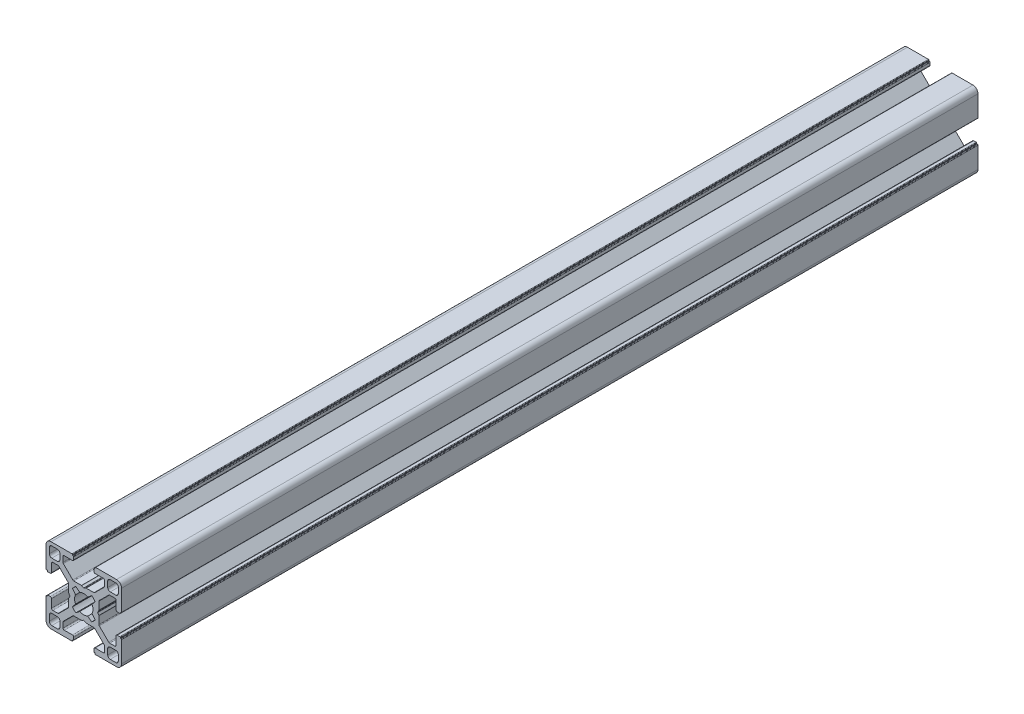
SolidWorks part; units mm, degrees
ref_plane "Alzado" through (0, 0, 0) normal (0, 0, 1) x (1, 0, 0)
ref_plane "Planta" through (0, 0, 0) normal (0, 1, 0) x (1, 0, 0)
ref_plane "Vista lateral" through (0, 0, 0) normal (1, 0, 0) x (0, 0, -1)
ref_plane "Plano1" through (0, 0, 1000) normal (0, 0, 1) x (1, 0, 0)
sketch "Croquis1" plane through (0, 0, 1000) normal (0, 0, 1) x (1, 0, 0)
  line L0 (8, -5.5) -> (5.8, -5.5)
  line L1 (4.8, -4.5) -> (4.8, -2.3)
  line L2 (5.8, -1.3) -> (8, -1.3)
  line L3 (9, -2.3) -> (9, -4.5)
  line L4 (-15.2, -5.5) -> (-17.4, -5.5)
  line L5 (-18.4, -4.5) -> (-18.4, -2.3)
  line L6 (-17.4, -1.3) -> (-15.2, -1.3)
  line L7 (-14.2, -2.3) -> (-14.2, -4.5)
  line L8 (-17.4, -24.5) -> (-15.2, -24.5)
  line L9 (-14.2, -25.5) -> (-14.2, -27.7)
  line L10 (-15.2, -28.7) -> (-17.4, -28.7)
  line L11 (-18.4, -27.7) -> (-18.4, -25.5)
  line L12 (5.8, -24.5) -> (8, -24.5)
  line L13 (9, -25.5) -> (9, -27.7)
  line L14 (8, -28.7) -> (5.8, -28.7)
  line L15 (4.8, -27.7) -> (4.8, -25.5)
  line L16 (-7.8359, -10.4816) -> (-6.3001, -11.7194)
  line L17 (-3.0999, -11.7194) -> (-1.5641, -10.4816)
  line L18 (-0.1947, -11.8453) -> (-1.4194, -13.3999)
  line L19 (-1.4194, -16.6001) -> (-0.1947, -18.1547)
  line L20 (-1.5641, -19.5184) -> (-3.0999, -18.2806)
  line L21 (-6.3001, -18.2806) -> (-7.8359, -19.5184)
  line L22 (-9.2053, -18.1547) -> (-7.9806, -16.6001)
  line L23 (-7.9806, -13.3999) -> (-9.2053, -11.8453)
  line L24 (9.8, -10.5) -> (10.1, -10.5)
  line L25 (10.3, -10.3) -> (10.3, -2)
  line L26 (8.3, 0) -> (0, 0)
  line L27 (-0.2, -0.2) -> (-0.2, -0.5)
  line L28 (-0.2, -0.5) -> (-0.5, -0.5)
  line L29 (-0.7, -0.7) -> (-0.7, -1.7)
  line L30 (-0.2, -2.2) -> (3.05, -2.2)
  line L31 (3.55, -2.7) -> (3.55, -4.7431)
  line L32 (3.4037, -5.0964) -> (-0.3491, -8.8534)
  line L33 (-0.7028, -9) -> (-3.7468, -9)
  line L34 (-3.8462, -9.0264) -> (-4.6006, -9.4583)
  line L35 (-4.7994, -9.4583) -> (-5.5538, -9.0264)
  line L36 (-5.6532, -9) -> (-8.6972, -9)
  line L37 (-9.0509, -8.8534) -> (-12.8037, -5.0964)
  line L38 (-12.95, -4.7431) -> (-12.95, -2.7)
  line L39 (-12.45, -2.2) -> (-9.2, -2.2)
  line L40 (-8.7, -1.7) -> (-8.7, -0.7)
  line L41 (-8.9, -0.5) -> (-9.2, -0.5)
  line L42 (-9.2, -0.5) -> (-9.2, -0.2)
  line L43 (-9.4, 0) -> (-17.7, 0)
  line L44 (-19.7, -2) -> (-19.7, -10.3)
  line L45 (-19.5, -10.5) -> (-19.2, -10.5)
  line L46 (-19.2, -10.5) -> (-19.2, -10.8)
  line L47 (-19, -11) -> (-18, -11)
  line L48 (-17.5, -10.5) -> (-17.5, -7.25)
  line L49 (-17, -6.75) -> (-14.9569, -6.75)
  line L50 (-14.6036, -6.8963) -> (-10.8466, -10.6491)
  line L51 (-10.7, -11.0028) -> (-10.7, -14.0468)
  line L52 (-10.6736, -14.1462) -> (-10.2417, -14.9006)
  line L53 (-10.2417, -15.0994) -> (-10.6736, -15.8538)
  line L54 (-10.7, -15.9532) -> (-10.7, -18.9972)
  line L55 (-10.8466, -19.3509) -> (-14.6036, -23.1037)
  line L56 (-14.9569, -23.25) -> (-17, -23.25)
  line L57 (-17.5, -22.75) -> (-17.5, -19.5)
  line L58 (-18, -19) -> (-19, -19)
  line L59 (-19.2, -19.2) -> (-19.2, -19.5)
  line L60 (-19.2, -19.5) -> (-19.5, -19.5)
  line L61 (-19.7, -19.7) -> (-19.7, -28)
  line L62 (-17.7, -30) -> (-9.4, -30)
  line L63 (-9.2, -29.8) -> (-9.2, -29.5)
  line L64 (-9.2, -29.5) -> (-8.9, -29.5)
  line L65 (-8.7, -29.3) -> (-8.7, -28.3)
  line L66 (-9.2, -27.8) -> (-12.45, -27.8)
  line L67 (-12.95, -27.3) -> (-12.95, -25.2569)
  line L68 (-12.8037, -24.9036) -> (-9.0509, -21.1466)
  line L69 (-8.6972, -21) -> (-5.6532, -21)
  line L70 (-5.5538, -20.9736) -> (-4.7994, -20.5417)
  line L71 (-4.6006, -20.5417) -> (-3.8462, -20.9736)
  line L72 (-3.7468, -21) -> (-0.7028, -21)
  line L73 (-0.3491, -21.1466) -> (3.4037, -24.9036)
  line L74 (3.55, -25.2569) -> (3.55, -27.3)
  line L75 (3.05, -27.8) -> (-0.2, -27.8)
  line L76 (-0.7, -28.3) -> (-0.7, -29.3)
  line L77 (-0.5, -29.5) -> (-0.2, -29.5)
  line L78 (-0.2, -29.5) -> (-0.2, -29.8)
  line L79 (0, -30) -> (8.3, -30)
  line L80 (10.3, -28) -> (10.3, -19.7)
  line L81 (10.1, -19.5) -> (9.8, -19.5)
  line L82 (9.8, -19.5) -> (9.8, -19.2)
  line L83 (9.6, -19) -> (8.6, -19)
  line L84 (8.1, -19.5) -> (8.1, -22.75)
  line L85 (7.6, -23.25) -> (5.5569, -23.25)
  line L86 (5.2036, -23.1037) -> (1.4466, -19.3509)
  line L87 (1.3, -18.9972) -> (1.3, -15.9532)
  line L88 (1.2736, -15.8538) -> (0.8417, -15.0994)
  line L89 (0.8417, -14.9006) -> (1.2736, -14.1462)
  line L90 (1.3, -14.0468) -> (1.3, -11.0028)
  line L91 (1.4466, -10.6491) -> (5.2036, -6.8963)
  line L92 (5.5569, -6.75) -> (7.6, -6.75)
  line L93 (8.1, -7.25) -> (8.1, -10.5)
  line L94 (8.6, -11) -> (9.6, -11)
  line L95 (9.8, -10.8) -> (9.8, -10.5)
  arc A0 (9, -4.5) -> (8, -5.5) centre (8, -4.5) cw
  arc A1 (5.8, -5.5) -> (4.8, -4.5) centre (5.8, -4.5) cw
  arc A2 (4.8, -2.3) -> (5.8, -1.3) centre (5.8, -2.3) cw
  arc A3 (8, -1.3) -> (9, -2.3) centre (8, -2.3) cw
  arc A4 (-14.2, -4.5) -> (-15.2, -5.5) centre (-15.2, -4.5) cw
  arc A5 (-17.4, -5.5) -> (-18.4, -4.5) centre (-17.4, -4.5) cw
  arc A6 (-18.4, -2.3) -> (-17.4, -1.3) centre (-17.4, -2.3) cw
  arc A7 (-15.2, -1.3) -> (-14.2, -2.3) centre (-15.2, -2.3) cw
  arc A8 (-18.4, -25.5) -> (-17.4, -24.5) centre (-17.4, -25.5) cw
  arc A9 (-15.2, -24.5) -> (-14.2, -25.5) centre (-15.2, -25.5) cw
  arc A10 (-14.2, -27.7) -> (-15.2, -28.7) centre (-15.2, -27.7) cw
  arc A11 (-17.4, -28.7) -> (-18.4, -27.7) centre (-17.4, -27.7) cw
  arc A12 (4.8, -25.5) -> (5.8, -24.5) centre (5.8, -25.5) cw
  arc A13 (8, -24.5) -> (9, -25.5) centre (8, -25.5) cw
  arc A14 (9, -27.7) -> (8, -28.7) centre (8, -27.7) cw
  arc A15 (5.8, -28.7) -> (4.8, -27.7) centre (5.8, -27.7) cw
  arc A16 (-9.2053, -11.8453) -> (-7.8359, -10.4816) centre (-4.7, -15) cw
  arc A17 (-6.3001, -11.7194) -> (-3.0999, -11.7194) centre (-4.7, -15) cw
  arc A18 (-1.5641, -10.4816) -> (-0.1947, -11.8453) centre (-4.7, -15) cw
  arc A19 (-1.4194, -13.3999) -> (-1.4194, -16.6001) centre (-4.7, -15) cw
  arc A20 (-0.1947, -18.1547) -> (-1.5641, -19.5184) centre (-4.7, -15) cw
  arc A21 (-3.0999, -18.2806) -> (-6.3001, -18.2806) centre (-4.7, -15) cw
  arc A22 (-7.8359, -19.5184) -> (-9.2053, -18.1547) centre (-4.7, -15) cw
  arc A23 (-7.9806, -16.6001) -> (-7.9806, -13.3999) centre (-4.7, -15) cw
  arc A24 (10.1, -10.5) -> (10.3, -10.3) centre (10.1, -10.3) ccw
  arc A25 (10.3, -2) -> (8.3, 0) centre (8.3, -2) ccw
  arc A26 (0, 0) -> (-0.2, -0.2) centre (0, -0.2) ccw
  arc A27 (-0.5, -0.5) -> (-0.7, -0.7) centre (-0.5, -0.7) ccw
  arc A28 (-0.7, -1.7) -> (-0.2, -2.2) centre (-0.2, -1.7) ccw
  arc A29 (3.05, -2.2) -> (3.55, -2.7) centre (3.05, -2.7) cw
  arc A30 (3.55, -4.7431) -> (3.4037, -5.0964) centre (3.05, -4.7431) cw
  arc A31 (-0.3491, -8.8534) -> (-0.7028, -9) centre (-0.7028, -8.5) cw
  arc A32 (-3.7468, -9) -> (-3.8462, -9.0264) centre (-3.7468, -9.2) ccw
  arc A33 (-4.6006, -9.4583) -> (-4.7994, -9.4583) centre (-4.7, -9.2847) cw
  arc A34 (-5.5538, -9.0264) -> (-5.6532, -9) centre (-5.6532, -9.2) ccw
  arc A35 (-8.6972, -9) -> (-9.0509, -8.8534) centre (-8.6972, -8.5) cw
  arc A36 (-12.8037, -5.0964) -> (-12.95, -4.7431) centre (-12.45, -4.7431) cw
  arc A37 (-12.95, -2.7) -> (-12.45, -2.2) centre (-12.45, -2.7) cw
  arc A38 (-9.2, -2.2) -> (-8.7, -1.7) centre (-9.2, -1.7) ccw
  arc A39 (-8.7, -0.7) -> (-8.9, -0.5) centre (-8.9, -0.7) ccw
  arc A40 (-9.2, -0.2) -> (-9.4, 0) centre (-9.4, -0.2) ccw
  arc A41 (-17.7, 0) -> (-19.7, -2) centre (-17.7, -2) ccw
  arc A42 (-19.7, -10.3) -> (-19.5, -10.5) centre (-19.5, -10.3) ccw
  arc A43 (-19.2, -10.8) -> (-19, -11) centre (-19, -10.8) ccw
  arc A44 (-18, -11) -> (-17.5, -10.5) centre (-18, -10.5) ccw
  arc A45 (-17.5, -7.25) -> (-17, -6.75) centre (-17, -7.25) cw
  arc A46 (-14.9569, -6.75) -> (-14.6036, -6.8963) centre (-14.9569, -7.25) cw
  arc A47 (-10.8466, -10.6491) -> (-10.7, -11.0028) centre (-11.2, -11.0028) cw
  arc A48 (-10.7, -14.0468) -> (-10.6736, -14.1462) centre (-10.5, -14.0468) ccw
  arc A49 (-10.2417, -14.9006) -> (-10.2417, -15.0994) centre (-10.4153, -15) cw
  arc A50 (-10.6736, -15.8538) -> (-10.7, -15.9532) centre (-10.5, -15.9532) ccw
  arc A51 (-10.7, -18.9972) -> (-10.8466, -19.3509) centre (-11.2, -18.9972) cw
  arc A52 (-14.6036, -23.1037) -> (-14.9569, -23.25) centre (-14.9569, -22.75) cw
  arc A53 (-17, -23.25) -> (-17.5, -22.75) centre (-17, -22.75) cw
  arc A54 (-17.5, -19.5) -> (-18, -19) centre (-18, -19.5) ccw
  arc A55 (-19, -19) -> (-19.2, -19.2) centre (-19, -19.2) ccw
  arc A56 (-19.5, -19.5) -> (-19.7, -19.7) centre (-19.5, -19.7) ccw
  arc A57 (-19.7, -28) -> (-17.7, -30) centre (-17.7, -28) ccw
  arc A58 (-9.4, -30) -> (-9.2, -29.8) centre (-9.4, -29.8) ccw
  arc A59 (-8.9, -29.5) -> (-8.7, -29.3) centre (-8.9, -29.3) ccw
  arc A60 (-8.7, -28.3) -> (-9.2, -27.8) centre (-9.2, -28.3) ccw
  arc A61 (-12.45, -27.8) -> (-12.95, -27.3) centre (-12.45, -27.3) cw
  arc A62 (-12.95, -25.2569) -> (-12.8037, -24.9036) centre (-12.45, -25.2569) cw
  arc A63 (-9.0509, -21.1466) -> (-8.6972, -21) centre (-8.6972, -21.5) cw
  arc A64 (-5.6532, -21) -> (-5.5538, -20.9736) centre (-5.6532, -20.8) ccw
  arc A65 (-4.7994, -20.5417) -> (-4.6006, -20.5417) centre (-4.7, -20.7153) cw
  arc A66 (-3.8462, -20.9736) -> (-3.7468, -21) centre (-3.7468, -20.8) ccw
  arc A67 (-0.7028, -21) -> (-0.3491, -21.1466) centre (-0.7028, -21.5) cw
  arc A68 (3.4037, -24.9036) -> (3.55, -25.2569) centre (3.05, -25.2569) cw
  arc A69 (3.55, -27.3) -> (3.05, -27.8) centre (3.05, -27.3) cw
  arc A70 (-0.2, -27.8) -> (-0.7, -28.3) centre (-0.2, -28.3) ccw
  arc A71 (-0.7, -29.3) -> (-0.5, -29.5) centre (-0.5, -29.3) ccw
  arc A72 (-0.2, -29.8) -> (0, -30) centre (0, -29.8) ccw
  arc A73 (8.3, -30) -> (10.3, -28) centre (8.3, -28) ccw
  arc A74 (10.3, -19.7) -> (10.1, -19.5) centre (10.1, -19.7) ccw
  arc A75 (9.8, -19.2) -> (9.6, -19) centre (9.6, -19.2) ccw
  arc A76 (8.6, -19) -> (8.1, -19.5) centre (8.6, -19.5) ccw
  arc A77 (8.1, -22.75) -> (7.6, -23.25) centre (7.6, -22.75) cw
  arc A78 (5.5569, -23.25) -> (5.2036, -23.1037) centre (5.5569, -22.75) cw
  arc A79 (1.4466, -19.3509) -> (1.3, -18.9972) centre (1.8, -18.9972) cw
  arc A80 (1.3, -15.9532) -> (1.2736, -15.8538) centre (1.1, -15.9532) ccw
  arc A81 (0.8417, -15.0994) -> (0.8417, -14.9006) centre (1.0153, -15) cw
  arc A82 (1.2736, -14.1462) -> (1.3, -14.0468) centre (1.1, -14.0468) ccw
  arc A83 (1.3, -11.0028) -> (1.4466, -10.6491) centre (1.8, -11.0028) cw
  arc A84 (5.2036, -6.8963) -> (5.5569, -6.75) centre (5.5569, -7.25) cw
  arc A85 (7.6, -6.75) -> (8.1, -7.25) centre (7.6, -7.25) cw
  arc A86 (8.1, -10.5) -> (8.6, -11) centre (8.6, -10.5) ccw
  arc A87 (9.6, -11) -> (9.8, -10.8) centre (9.6, -10.8) ccw
extrude "Saliente-Extruir1" add sketch "Croquis1" against normal blind 1000
sketch "Croquis4" plane through (0, 0, 0) normal (0, 0, -1) x (-1, 0, 0)
  line L72 (-9.8, -10.5) -> (-9.8, -10.8)
  line L73 (-9.6, -11) -> (-8.6, -11)
  line L74 (-8.1, -10.5) -> (-8.1, -7.25)
  line L75 (-7.6, -6.75) -> (-5.5569, -6.75)
  line L76 (-5.2036, -6.8963) -> (-1.4466, -10.6491)
  line L77 (-1.3, -11.0028) -> (-1.3, -14.0468)
  line L78 (-1.2736, -14.1462) -> (-0.8417, -14.9006)
  line L79 (-0.8417, -15.0994) -> (-1.2736, -15.8538)
  line L80 (-1.3, -15.9532) -> (-1.3, -18.9972)
  line L81 (-1.4466, -19.3509) -> (-5.2036, -23.1037)
  line L82 (-5.5569, -23.25) -> (-7.6, -23.25)
  line L83 (-8.1, -22.75) -> (-8.1, -19.5)
  line L84 (-8.6, -19) -> (-9.6, -19)
  line L85 (-9.8, -19.2) -> (-9.8, -19.5)
  line L86 (-9.8, -19.5) -> (-10.1, -19.5)
  line L87 (-10.3, -19.7) -> (-10.3, -28)
  line L88 (-8.3, -30) -> (0, -30)
  line L89 (0.2, -29.8) -> (0.2, -29.5)
  line L90 (0.2, -29.5) -> (0.5, -29.5)
  line L91 (0.7, -29.3) -> (0.7, -28.3)
  line L92 (0.2, -27.8) -> (-3.05, -27.8)
  line L93 (-3.55, -27.3) -> (-3.55, -25.2569)
  line L94 (-3.4037, -24.9036) -> (0.3491, -21.1466)
  line L95 (0.7028, -21) -> (3.7468, -21)
  line L96 (3.8462, -20.9736) -> (4.6006, -20.5417)
  line L97 (4.7994, -20.5417) -> (5.5538, -20.9736)
  line L98 (5.6532, -21) -> (8.6972, -21)
  line L99 (9.0509, -21.1466) -> (12.8037, -24.9036)
  line L100 (12.95, -25.2569) -> (12.95, -27.3)
  line L101 (12.45, -27.8) -> (9.2, -27.8)
  line L102 (8.7, -28.3) -> (8.7, -29.3)
  line L103 (8.9, -29.5) -> (9.2, -29.5)
  line L104 (9.2, -29.5) -> (9.2, -29.8)
  line L105 (9.4, -30) -> (17.7, -30)
  line L106 (19.7, -28) -> (19.7, -19.7)
  line L107 (19.5, -19.5) -> (19.2, -19.5)
  line L108 (19.2, -19.5) -> (19.2, -19.2)
  line L109 (19, -19) -> (18, -19)
  line L110 (17.5, -19.5) -> (17.5, -22.75)
  line L111 (17, -23.25) -> (14.9569, -23.25)
  line L112 (14.6036, -23.1037) -> (10.8466, -19.3509)
  line L113 (10.7, -18.9972) -> (10.7, -15.9532)
  line L114 (10.6736, -15.8538) -> (10.2417, -15.0994)
  line L115 (10.2417, -14.9006) -> (10.6736, -14.1462)
  line L116 (10.7, -14.0468) -> (10.7, -11.0028)
  line L117 (10.8466, -10.6491) -> (14.6036, -6.8963)
  line L118 (14.9569, -6.75) -> (17, -6.75)
  line L119 (17.5, -7.25) -> (17.5, -10.5)
  line L120 (18, -11) -> (19, -11)
  line L121 (19.2, -10.8) -> (19.2, -10.5)
  line L122 (19.2, -10.5) -> (19.5, -10.5)
  line L123 (19.7, -10.3) -> (19.7, -2)
  line L124 (17.7, 0) -> (9.4, 0)
  line L125 (9.2, -0.2) -> (9.2, -0.5)
  line L126 (9.2, -0.5) -> (8.9, -0.5)
  line L127 (8.7, -0.7) -> (8.7, -1.7)
  line L128 (9.2, -2.2) -> (12.45, -2.2)
  line L129 (12.95, -2.7) -> (12.95, -4.7431)
  line L130 (12.8037, -5.0964) -> (9.0509, -8.8534)
  line L131 (8.6972, -9) -> (5.6532, -9)
  line L132 (5.5538, -9.0264) -> (4.7994, -9.4583)
  line L133 (4.6006, -9.4583) -> (3.8462, -9.0264)
  line L134 (3.7468, -9) -> (0.7028, -9)
  line L135 (0.3491, -8.8534) -> (-3.4037, -5.0964)
  line L136 (-3.55, -4.7431) -> (-3.55, -2.7)
  line L137 (-3.05, -2.2) -> (0.2, -2.2)
  line L138 (0.7, -1.7) -> (0.7, -0.7)
  line L139 (0.5, -0.5) -> (0.2, -0.5)
  line L140 (0.2, -0.5) -> (0.2, -0.2)
  line L141 (0, 0) -> (-8.3, 0)
  line L142 (-10.3, -2) -> (-10.3, -10.3)
  line L143 (-10.1, -10.5) -> (-9.8, -10.5)
  line L144 (-9.8, -10.5) -> (-9.8, -10.8)
  line L145 (-9.6, -11) -> (-8.6, -11)
  line L146 (-8.1, -10.5) -> (-8.1, -7.25)
  line L147 (-7.6, -6.75) -> (-5.5569, -6.75)
  line L148 (-5.2036, -6.8963) -> (-1.4466, -10.6491)
  line L149 (-1.3, -11.0028) -> (-1.3, -14.0468)
  line L150 (-1.2736, -14.1462) -> (-0.8417, -14.9006)
  line L151 (-0.8417, -15.0994) -> (-1.2736, -15.8538)
  line L152 (-1.3, -15.9532) -> (-1.3, -18.9972)
  line L153 (-1.4466, -19.3509) -> (-5.2036, -23.1037)
  line L154 (-5.5569, -23.25) -> (-7.6, -23.25)
  line L155 (-8.1, -22.75) -> (-8.1, -19.5)
  line L156 (-8.6, -19) -> (-9.6, -19)
  line L157 (-9.8, -19.2) -> (-9.8, -19.5)
  line L158 (-9.8, -19.5) -> (-10.1, -19.5)
  line L159 (-10.3, -19.7) -> (-10.3, -28)
  line L160 (-8.3, -30) -> (0, -30)
  line L161 (0.2, -29.8) -> (0.2, -29.5)
  line L162 (0.2, -29.5) -> (0.5, -29.5)
  line L163 (0.7, -29.3) -> (0.7, -28.3)
  line L164 (0.2, -27.8) -> (-3.05, -27.8)
  line L165 (-3.55, -27.3) -> (-3.55, -25.2569)
  line L166 (-3.4037, -24.9036) -> (0.3491, -21.1466)
  line L167 (0.7028, -21) -> (3.7468, -21)
  line L168 (3.8462, -20.9736) -> (4.6006, -20.5417)
  line L169 (4.7994, -20.5417) -> (5.5538, -20.9736)
  line L170 (5.6532, -21) -> (8.6972, -21)
  line L171 (9.0509, -21.1466) -> (12.8037, -24.9036)
  line L172 (12.95, -25.2569) -> (12.95, -27.3)
  line L173 (12.45, -27.8) -> (9.2, -27.8)
  line L174 (8.7, -28.3) -> (8.7, -29.3)
  line L175 (8.9, -29.5) -> (9.2, -29.5)
  line L176 (9.2, -29.5) -> (9.2, -29.8)
  line L177 (9.4, -30) -> (17.7, -30)
  line L178 (19.7, -28) -> (19.7, -19.7)
  line L179 (19.5, -19.5) -> (19.2, -19.5)
  line L180 (19.2, -19.5) -> (19.2, -19.2)
  line L181 (19, -19) -> (18, -19)
  line L182 (17.5, -19.5) -> (17.5, -22.75)
  line L183 (17, -23.25) -> (14.9569, -23.25)
  line L184 (14.6036, -23.1037) -> (10.8466, -19.3509)
  line L185 (10.7, -18.9972) -> (10.7, -15.9532)
  line L186 (10.6736, -15.8538) -> (10.2417, -15.0994)
  line L187 (10.2417, -14.9006) -> (10.6736, -14.1462)
  line L188 (10.7, -14.0468) -> (10.7, -11.0028)
  line L189 (10.8466, -10.6491) -> (14.6036, -6.8963)
  line L190 (14.9569, -6.75) -> (17, -6.75)
  line L191 (17.5, -7.25) -> (17.5, -10.5)
  line L192 (18, -11) -> (19, -11)
  line L193 (19.2, -10.8) -> (19.2, -10.5)
  line L194 (19.2, -10.5) -> (19.5, -10.5)
  line L195 (19.7, -10.3) -> (19.7, -2)
  line L196 (17.7, 0) -> (9.4, 0)
  line L197 (9.2, -0.2) -> (9.2, -0.5)
  line L198 (9.2, -0.5) -> (8.9, -0.5)
  line L199 (8.7, -0.7) -> (8.7, -1.7)
  line L200 (9.2, -2.2) -> (12.45, -2.2)
  line L201 (12.95, -2.7) -> (12.95, -4.7431)
  line L202 (12.8037, -5.0964) -> (9.0509, -8.8534)
  line L203 (8.6972, -9) -> (5.6532, -9)
  line L204 (5.5538, -9.0264) -> (4.7994, -9.4583)
  line L205 (4.6006, -9.4583) -> (3.8462, -9.0264)
  line L206 (3.7468, -9) -> (0.7028, -9)
  line L207 (0.3491, -8.8534) -> (-3.4037, -5.0964)
  line L208 (-3.55, -4.7431) -> (-3.55, -2.7)
  line L209 (-3.05, -2.2) -> (0.2, -2.2)
  line L210 (0.7, -1.7) -> (0.7, -0.7)
  line L211 (0.5, -0.5) -> (0.2, -0.5)
  line L212 (0.2, -0.5) -> (0.2, -0.2)
  line L213 (0, 0) -> (-8.3, 0)
  line L214 (-10.3, -2) -> (-10.3, -10.3)
  line L215 (-10.1, -10.5) -> (-9.8, -10.5)
  arc A64 (-9.8, -10.8) -> (-9.6, -11) centre (-9.6, -10.8) ccw
  arc A65 (-8.6, -11) -> (-8.1, -10.5) centre (-8.6, -10.5) ccw
  arc A66 (-7.6, -6.75) -> (-8.1, -7.25) centre (-7.6, -7.25) ccw
  arc A67 (-5.2036, -6.8963) -> (-5.5569, -6.75) centre (-5.5569, -7.25) ccw
  arc A68 (-1.3, -11.0028) -> (-1.4466, -10.6491) centre (-1.8, -11.0028) ccw
  arc A69 (-1.3, -14.0468) -> (-1.2736, -14.1462) centre (-1.1, -14.0468) ccw
  arc A70 (-0.8417, -15.0994) -> (-0.8417, -14.9006) centre (-1.0153, -15) ccw
  arc A71 (-1.2736, -15.8538) -> (-1.3, -15.9532) centre (-1.1, -15.9532) ccw
  arc A72 (-1.4466, -19.3509) -> (-1.3, -18.9972) centre (-1.8, -18.9972) ccw
  arc A73 (-5.5569, -23.25) -> (-5.2036, -23.1037) centre (-5.5569, -22.75) ccw
  arc A74 (-8.1, -22.75) -> (-7.6, -23.25) centre (-7.6, -22.75) ccw
  arc A75 (-8.1, -19.5) -> (-8.6, -19) centre (-8.6, -19.5) ccw
  arc A76 (-9.6, -19) -> (-9.8, -19.2) centre (-9.6, -19.2) ccw
  arc A77 (-10.1, -19.5) -> (-10.3, -19.7) centre (-10.1, -19.7) ccw
  arc A78 (-10.3, -28) -> (-8.3, -30) centre (-8.3, -28) ccw
  arc A79 (0, -30) -> (0.2, -29.8) centre (0, -29.8) ccw
  arc A80 (0.5, -29.5) -> (0.7, -29.3) centre (0.5, -29.3) ccw
  arc A81 (0.7, -28.3) -> (0.2, -27.8) centre (0.2, -28.3) ccw
  arc A82 (-3.55, -27.3) -> (-3.05, -27.8) centre (-3.05, -27.3) ccw
  arc A83 (-3.4037, -24.9036) -> (-3.55, -25.2569) centre (-3.05, -25.2569) ccw
  arc A84 (0.7028, -21) -> (0.3491, -21.1466) centre (0.7028, -21.5) ccw
  arc A85 (3.7468, -21) -> (3.8462, -20.9736) centre (3.7468, -20.8) ccw
  arc A86 (4.7994, -20.5417) -> (4.6006, -20.5417) centre (4.7, -20.7153) ccw
  arc A87 (5.5538, -20.9736) -> (5.6532, -21) centre (5.6532, -20.8) ccw
  arc A88 (9.0509, -21.1466) -> (8.6972, -21) centre (8.6972, -21.5) ccw
  arc A89 (12.95, -25.2569) -> (12.8037, -24.9036) centre (12.45, -25.2569) ccw
  arc A90 (12.45, -27.8) -> (12.95, -27.3) centre (12.45, -27.3) ccw
  arc A91 (9.2, -27.8) -> (8.7, -28.3) centre (9.2, -28.3) ccw
  arc A92 (8.7, -29.3) -> (8.9, -29.5) centre (8.9, -29.3) ccw
  arc A93 (9.2, -29.8) -> (9.4, -30) centre (9.4, -29.8) ccw
  arc A94 (17.7, -30) -> (19.7, -28) centre (17.7, -28) ccw
  arc A95 (19.7, -19.7) -> (19.5, -19.5) centre (19.5, -19.7) ccw
  arc A96 (19.2, -19.2) -> (19, -19) centre (19, -19.2) ccw
  arc A97 (18, -19) -> (17.5, -19.5) centre (18, -19.5) ccw
  arc A98 (17, -23.25) -> (17.5, -22.75) centre (17, -22.75) ccw
  arc A99 (14.6036, -23.1037) -> (14.9569, -23.25) centre (14.9569, -22.75) ccw
  arc A100 (10.7, -18.9972) -> (10.8466, -19.3509) centre (11.2, -18.9972) ccw
  arc A101 (10.7, -15.9532) -> (10.6736, -15.8538) centre (10.5, -15.9532) ccw
  arc A102 (10.2417, -14.9006) -> (10.2417, -15.0994) centre (10.4153, -15) ccw
  arc A103 (10.6736, -14.1462) -> (10.7, -14.0468) centre (10.5, -14.0468) ccw
  arc A104 (10.8466, -10.6491) -> (10.7, -11.0028) centre (11.2, -11.0028) ccw
  arc A105 (14.9569, -6.75) -> (14.6036, -6.8963) centre (14.9569, -7.25) ccw
  arc A106 (17.5, -7.25) -> (17, -6.75) centre (17, -7.25) ccw
  arc A107 (17.5, -10.5) -> (18, -11) centre (18, -10.5) ccw
  arc A108 (19, -11) -> (19.2, -10.8) centre (19, -10.8) ccw
  arc A109 (19.5, -10.5) -> (19.7, -10.3) centre (19.5, -10.3) ccw
  arc A110 (19.7, -2) -> (17.7, 0) centre (17.7, -2) ccw
  arc A111 (9.4, 0) -> (9.2, -0.2) centre (9.4, -0.2) ccw
  arc A112 (8.9, -0.5) -> (8.7, -0.7) centre (8.9, -0.7) ccw
  arc A113 (8.7, -1.7) -> (9.2, -2.2) centre (9.2, -1.7) ccw
  arc A114 (12.95, -2.7) -> (12.45, -2.2) centre (12.45, -2.7) ccw
  arc A115 (12.8037, -5.0964) -> (12.95, -4.7431) centre (12.45, -4.7431) ccw
  arc A116 (8.6972, -9) -> (9.0509, -8.8534) centre (8.6972, -8.5) ccw
  arc A117 (5.6532, -9) -> (5.5538, -9.0264) centre (5.6532, -9.2) ccw
  arc A118 (4.6006, -9.4583) -> (4.7994, -9.4583) centre (4.7, -9.2847) ccw
  arc A119 (3.8462, -9.0264) -> (3.7468, -9) centre (3.7468, -9.2) ccw
  arc A120 (0.3491, -8.8534) -> (0.7028, -9) centre (0.7028, -8.5) ccw
  arc A121 (-3.55, -4.7431) -> (-3.4037, -5.0964) centre (-3.05, -4.7431) ccw
  arc A122 (-3.05, -2.2) -> (-3.55, -2.7) centre (-3.05, -2.7) ccw
  arc A123 (0.2, -2.2) -> (0.7, -1.7) centre (0.2, -1.7) ccw
  arc A124 (0.7, -0.7) -> (0.5, -0.5) centre (0.5, -0.7) ccw
  arc A125 (0.2, -0.2) -> (0, 0) centre (0, -0.2) ccw
  arc A126 (-8.3, 0) -> (-10.3, -2) centre (-8.3, -2) ccw
  arc A127 (-10.3, -10.3) -> (-10.1, -10.5) centre (-10.1, -10.3) ccw
  arc A128 (-9.8, -10.8) -> (-9.6, -11) centre (-9.6, -10.8) ccw
  arc A129 (-8.6, -11) -> (-8.1, -10.5) centre (-8.6, -10.5) ccw
  arc A130 (-7.6, -6.75) -> (-8.1, -7.25) centre (-7.6, -7.25) ccw
  arc A131 (-5.2036, -6.8963) -> (-5.5569, -6.75) centre (-5.5569, -7.25) ccw
  arc A132 (-1.3, -11.0028) -> (-1.4466, -10.6491) centre (-1.8, -11.0028) ccw
  arc A133 (-1.3, -14.0468) -> (-1.2736, -14.1462) centre (-1.1, -14.0468) ccw
  arc A134 (-0.8417, -15.0994) -> (-0.8417, -14.9006) centre (-1.0153, -15) ccw
  arc A135 (-1.2736, -15.8538) -> (-1.3, -15.9532) centre (-1.1, -15.9532) ccw
  arc A136 (-1.4466, -19.3509) -> (-1.3, -18.9972) centre (-1.8, -18.9972) ccw
  arc A137 (-5.5569, -23.25) -> (-5.2036, -23.1037) centre (-5.5569, -22.75) ccw
  arc A138 (-8.1, -22.75) -> (-7.6, -23.25) centre (-7.6, -22.75) ccw
  arc A139 (-8.1, -19.5) -> (-8.6, -19) centre (-8.6, -19.5) ccw
  arc A140 (-9.6, -19) -> (-9.8, -19.2) centre (-9.6, -19.2) ccw
  arc A141 (-10.1, -19.5) -> (-10.3, -19.7) centre (-10.1, -19.7) ccw
  arc A142 (-10.3, -28) -> (-8.3, -30) centre (-8.3, -28) ccw
  arc A143 (0, -30) -> (0.2, -29.8) centre (0, -29.8) ccw
  arc A144 (0.5, -29.5) -> (0.7, -29.3) centre (0.5, -29.3) ccw
  arc A145 (0.7, -28.3) -> (0.2, -27.8) centre (0.2, -28.3) ccw
  arc A146 (-3.55, -27.3) -> (-3.05, -27.8) centre (-3.05, -27.3) ccw
  arc A147 (-3.4037, -24.9036) -> (-3.55, -25.2569) centre (-3.05, -25.2569) ccw
  arc A148 (0.7028, -21) -> (0.3491, -21.1466) centre (0.7028, -21.5) ccw
  arc A149 (3.7468, -21) -> (3.8462, -20.9736) centre (3.7468, -20.8) ccw
  arc A150 (4.7994, -20.5417) -> (4.6006, -20.5417) centre (4.7, -20.7153) ccw
  arc A151 (5.5538, -20.9736) -> (5.6532, -21) centre (5.6532, -20.8) ccw
  arc A152 (9.0509, -21.1466) -> (8.6972, -21) centre (8.6972, -21.5) ccw
  arc A153 (12.95, -25.2569) -> (12.8037, -24.9036) centre (12.45, -25.2569) ccw
  arc A154 (12.45, -27.8) -> (12.95, -27.3) centre (12.45, -27.3) ccw
  arc A155 (9.2, -27.8) -> (8.7, -28.3) centre (9.2, -28.3) ccw
  arc A156 (8.7, -29.3) -> (8.9, -29.5) centre (8.9, -29.3) ccw
  arc A157 (9.2, -29.8) -> (9.4, -30) centre (9.4, -29.8) ccw
  arc A158 (17.7, -30) -> (19.7, -28) centre (17.7, -28) ccw
  arc A159 (19.7, -19.7) -> (19.5, -19.5) centre (19.5, -19.7) ccw
  arc A160 (19.2, -19.2) -> (19, -19) centre (19, -19.2) ccw
  arc A161 (18, -19) -> (17.5, -19.5) centre (18, -19.5) ccw
  arc A162 (17, -23.25) -> (17.5, -22.75) centre (17, -22.75) ccw
  arc A163 (14.6036, -23.1037) -> (14.9569, -23.25) centre (14.9569, -22.75) ccw
  arc A164 (10.7, -18.9972) -> (10.8466, -19.3509) centre (11.2, -18.9972) ccw
  arc A165 (10.7, -15.9532) -> (10.6736, -15.8538) centre (10.5, -15.9532) ccw
  arc A166 (10.2417, -14.9006) -> (10.2417, -15.0994) centre (10.4153, -15) ccw
  arc A167 (10.6736, -14.1462) -> (10.7, -14.0468) centre (10.5, -14.0468) ccw
  arc A168 (10.8466, -10.6491) -> (10.7, -11.0028) centre (11.2, -11.0028) ccw
  arc A169 (14.9569, -6.75) -> (14.6036, -6.8963) centre (14.9569, -7.25) ccw
  arc A170 (17.5, -7.25) -> (17, -6.75) centre (17, -7.25) ccw
  arc A171 (17.5, -10.5) -> (18, -11) centre (18, -10.5) ccw
  arc A172 (19, -11) -> (19.2, -10.8) centre (19, -10.8) ccw
  arc A173 (19.5, -10.5) -> (19.7, -10.3) centre (19.5, -10.3) ccw
  arc A174 (19.7, -2) -> (17.7, 0) centre (17.7, -2) ccw
  arc A175 (9.4, 0) -> (9.2, -0.2) centre (9.4, -0.2) ccw
  arc A176 (8.9, -0.5) -> (8.7, -0.7) centre (8.9, -0.7) ccw
  arc A177 (8.7, -1.7) -> (9.2, -2.2) centre (9.2, -1.7) ccw
  arc A178 (12.95, -2.7) -> (12.45, -2.2) centre (12.45, -2.7) ccw
  arc A179 (12.8037, -5.0964) -> (12.95, -4.7431) centre (12.45, -4.7431) ccw
  arc A180 (8.6972, -9) -> (9.0509, -8.8534) centre (8.6972, -8.5) ccw
  arc A181 (5.6532, -9) -> (5.5538, -9.0264) centre (5.6532, -9.2) ccw
  arc A182 (4.6006, -9.4583) -> (4.7994, -9.4583) centre (4.7, -9.2847) ccw
  arc A183 (3.8462, -9.0264) -> (3.7468, -9) centre (3.7468, -9.2) ccw
  arc A184 (0.3491, -8.8534) -> (0.7028, -9) centre (0.7028, -8.5) ccw
  arc A185 (-3.55, -4.7431) -> (-3.4037, -5.0964) centre (-3.05, -4.7431) ccw
  arc A186 (-3.05, -2.2) -> (-3.55, -2.7) centre (-3.05, -2.7) ccw
  arc A187 (0.2, -2.2) -> (0.7, -1.7) centre (0.2, -1.7) ccw
  arc A188 (0.7, -0.7) -> (0.5, -0.5) centre (0.5, -0.7) ccw
  arc A189 (0.2, -0.2) -> (0, 0) centre (0, -0.2) ccw
  arc A190 (-8.3, 0) -> (-10.3, -2) centre (-8.3, -2) ccw
  arc A191 (-10.3, -10.3) -> (-10.1, -10.5) centre (-10.1, -10.3) ccw
  point P2 (0, 0)
  dimension "D1" = 0
extrude "Cortar-Extruir1" cut sketch "Croquis4" against normal blind 660
